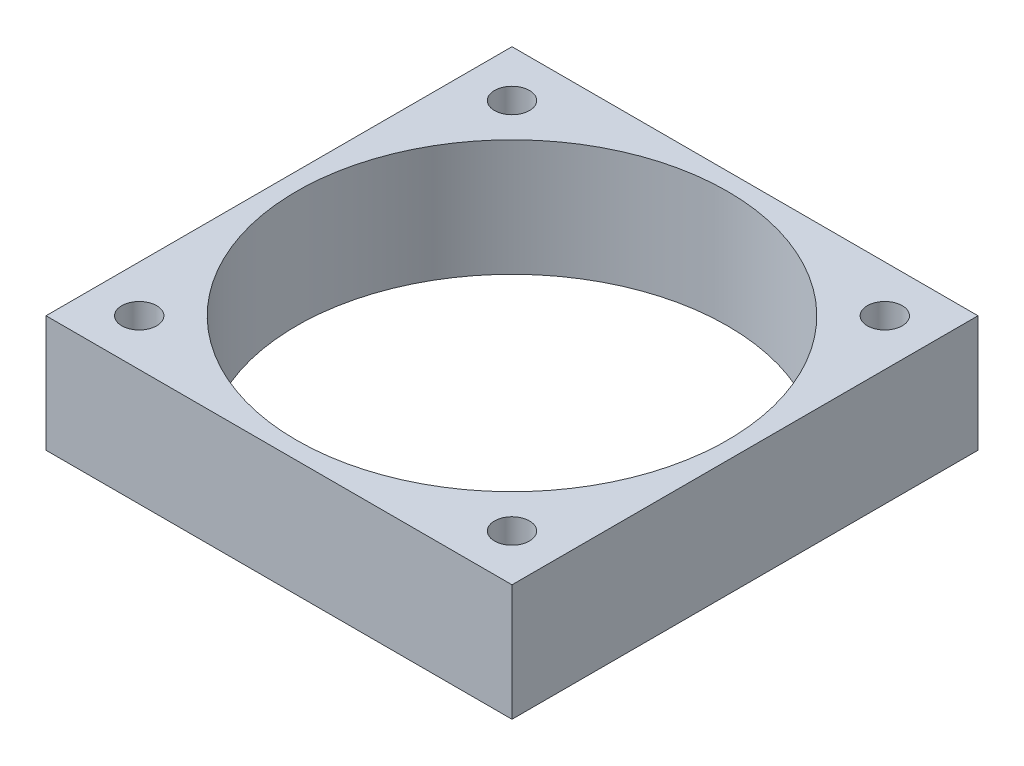
SolidWorks part; units mm, degrees
ref_plane "Front Plane" through (0, 0, 0) normal (0, 0, 1) x (1, 0, 0)
ref_plane "Top Plane" through (0, 0, 0) normal (0, 1, 0) x (1, 0, 0)
ref_plane "Right Plane" through (0, 0, 0) normal (1, 0, 0) x (0, 0, -1)
sketch "Sketch1" plane through (0, 0, 0) normal (0, 1, 0) x (1, 0, 0)
  line L1 (0, 0) -> (40, 0)
  line L2 (0, 0) -> (0, -40)
  line L3 (0, -40) -> (40, -40)
  line L4 (40, 0) -> (40, -40)
  dimension "D1" = 40
  dimension "D2" = 40
extrude "Boss-Extrude1" add sketch "Sketch1" along normal blind 10
sketch "Sketch2" plane through (0, 10, 0) normal (0, 1, 0) x (1, 0, 0)
  line L0 (0, -40) -> (40, -40) construction
  line L1 (0, 0) -> (0, -40) construction
  circle A0 centre (4, -36) radius 1.5
  circle A1 centre (36, -36) radius 1.5
  circle A2 centre (36, -4) radius 1.5
  circle A3 centre (4, -4) radius 1.5
  dimension "D3" = 3
  dimension "D1" = 4
  dimension "D2" = 4
  dimension "D4" = 2
  dimension "D5" = 2
extrude "Cut-Extrude1" cut sketch "Sketch2" against normal through all
sketch "Sketch3" plane through (0, 10, 0) normal (0, 1, 0) x (1, 0, 0)
  circle A0 centre (20, -20) radius 18.5
  dimension "D1" = 37
extrude "Cut-Extrude2" cut sketch "Sketch3" against normal blind 10
